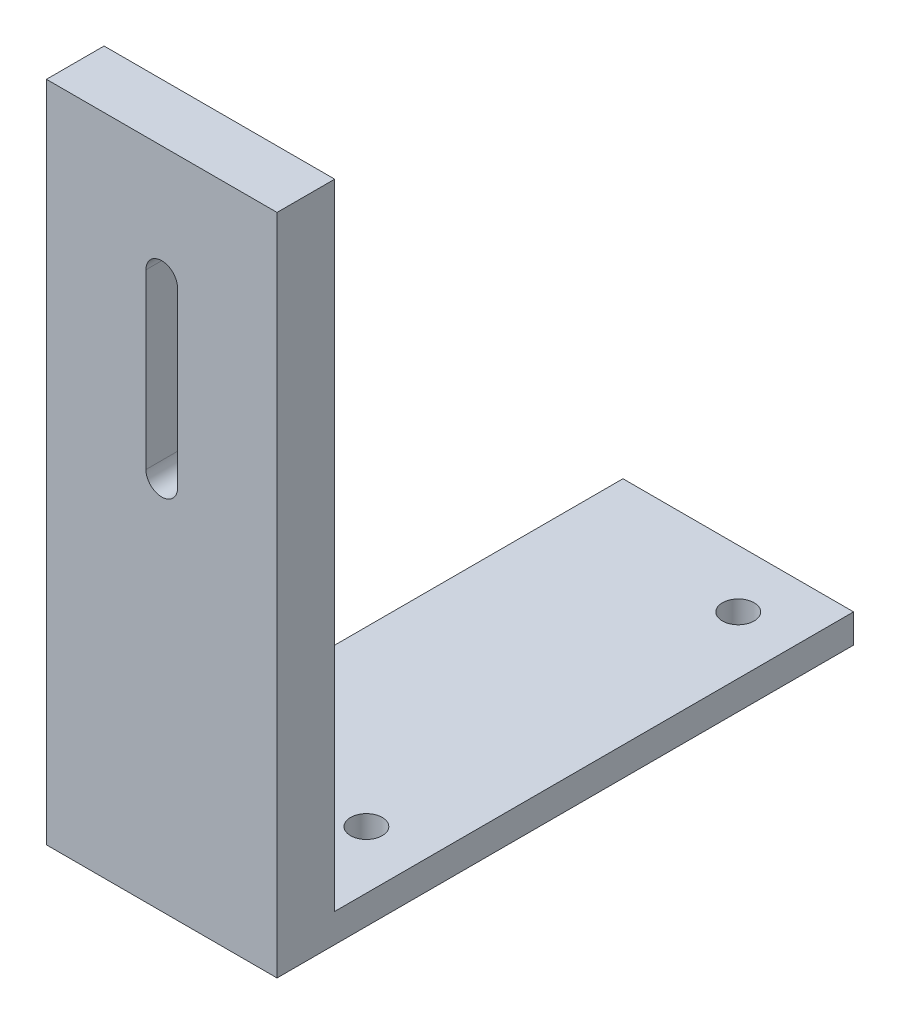
SolidWorks part; units mm, degrees
ref_plane "前基準面" through (0, 0, 0) normal (0, 0, 1) x (1, 0, 0)
ref_plane "上基準面" through (0, 0, 0) normal (0, 1, 0) x (1, 0, 0)
ref_plane "右基準面" through (0, 0, 0) normal (1, 0, 0) x (0, 0, -1)
sketch "草圖1" plane through (0, 0, 0) normal (0, 0, 1) x (1, 0, 0)
  line L1 (-23.0571, 5) -> (16.9429, 5)
  line L2 (-23.0571, 5) -> (-23.0571, 0)
  line L3 (-23.0571, 0) -> (16.9429, 0)
  line L4 (16.9429, 5) -> (16.9429, 0)
  line L5 (-23.0571, 5) -> (16.9429, 0) construction
  line L6 (-23.0571, 0) -> (16.9429, 5) construction
  point P0 (-3.0571, 2.5)
  dimension "D1" = 5
  dimension "D2" = 40
extrude "填料-伸長1" add sketch "草圖1" along normal blind 100
sketch "草圖3" plane through (0, 5, 0) normal (0, 1, 0) x (1, 0, 0)
  line L0 (16.9429, 0) -> (-23.0571, 0) construction
  line L1 (16.9429, -100) -> (16.9429, 0) construction
  circle A0 centre (6.9429, -10) radius 2.75
  circle A1 centre (6.9429, -74.5) radius 2.75
  dimension "D1" = 5.5
  dimension "D2" = 5.5
  dimension "D6" = 64.5
  dimension "D3" = 10
  dimension "D4" = 10
  dimension "D5" = 10
extrude "除料-伸長1" cut sketch "草圖3" against normal through all
sketch "草圖5" plane through (0, 5, 0) normal (0, 1, 0) x (1, 0, 0)
  line L0 (16.9429, -100) -> (16.9429, 0) construction
  line L1 (-23.0571, -100) -> (16.9429, -100)
  line L2 (-23.0571, -100) -> (-23.0571, -90)
  line L3 (-23.0571, -90) -> (16.9429, -90)
  line L4 (16.9429, -100) -> (16.9429, -90)
  dimension "D1" = 10
extrude "填料-伸長2" add sketch "草圖5" along normal blind 110
sketch "草圖7" plane through (0, 0, 90) normal (0, 0, -1) x (-1, 0, 0)
  line L0 (-16.9429, 5) -> (23.0571, 5) construction
  line L1 (-16.9429, 115) -> (-16.9429, 5) construction
  line L4 (5.8071, 95) -> (5.8071, 65)
  line L6 (0.3071, 95) -> (0.3071, 65)
  arc A0 (5.8071, 95) -> (0.3071, 95) centre (3.0571, 95) ccw
  arc A1 (0.3071, 65) -> (5.8071, 65) centre (3.0571, 65) ccw
  dimension "D1" = 5.5
  dimension "D2" = 5.5
  dimension "D3" = 60
  dimension "D4" = 90
  dimension "D5" = 20
  dimension "D6" = 20
extrude "除料-伸長2" cut sketch "草圖7" against normal through all
